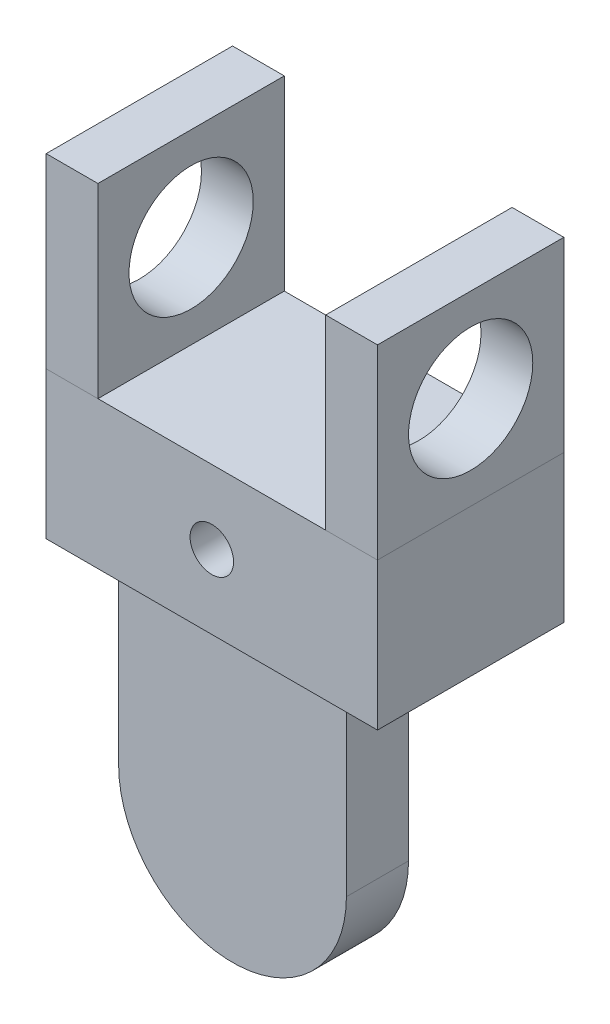
SolidWorks part; units mm, degrees
ref_plane "Front Plane" through (0, 0, 0) normal (0, 0, 1) x (1, 0, 0)
ref_plane "Top Plane" through (0, 0, 0) normal (0, 1, 0) x (1, 0, 0)
ref_plane "Right Plane" through (0, 0, 0) normal (1, 0, 0) x (0, 0, -1)
sketch "Sketch1" plane through (0, 0, 0) normal (0, 0, 1) x (1, 0, 0)
  circle A0 centre (0, 0) radius 1.505
  dimension "D1" = 3.01
extrude "Boss-Extrude1" add sketch "Sketch1" along normal blind 3.1
sketch "Sketch2" plane through (0, 0, 3.1) normal (0, 0, 1) x (1, 0, 0)
  line L0 (-5.5, 0) -> (-5.5, 8.72)
  line L1 (5.5, 0) -> (5.5, 8.72)
  line L2 (-5.5, 8.72) -> (5.5, 8.72)
  circle A1 centre (0, 0) radius 5.5
  circle M3 centre (0, 0) radius 1.505
  dimension "D1" = 11
  dimension "D2" = 8.72
  dimension "D3" = 8.72
extrude "Boss-Extrude2" add sketch "Sketch2" along normal blind 3 separate body contours A1 M3 | M3 | A1 L1 L2 L0
sketch "Sketch3" plane through (0, 8.72, 0) normal (0, 1, 0) x (1, 0, 0)
  line L0 (-5.5, -6.1) -> (-8, -6.1)
  line L1 (5.5, -6.1) -> (8, -6.1)
  line L2 (8, -6.1) -> (8, -7.1)
  line L3 (-8, -6.1) -> (8, -6.1)
  line L4 (-8, -6.1) -> (-8, 1.9)
  line L5 (-8, 1.9) -> (8, 1.9)
  line L6 (8, -6.1) -> (8, 1.9)
  line L7 (-8, -6.1) -> (-8, -7.1)
  line L8 (-8, -7.1) -> (8, -7.1)
  line M7 (5.5, -3.1) -> (-5.5, -3.1)
  line M8 (-5.5, -3.1) -> (-5.5, -6.1)
  line M9 (-5.5, -6.1) -> (5.5, -6.1)
  line M10 (5.5, -6.1) -> (5.5, -3.1)
  dimension "D1" = 2.5
  dimension "D2" = 2.5
  dimension "D3" = 8
  dimension "D4" = 1
  dimension "D5" = 1
extrude "Boss-Extrude4" add sketch "Sketch3" along normal blind 7.11 separate body contours M10 M7 M8 M9 | L1 L6 L5 L4 L0 M8 M7 M10 | L7 L8 L2 L1 L0 M9
sketch3d "3DSketch1"
  line L0 (-8, 15.83, 2.6) -> (-8, 20.33, 2.6) construction
  line L1 (-8, 15.83, -1.9) -> (-8, 24.83, -1.9)
  line L2 (-8, 15.83, -1.9) -> (-8, 15.83, 7.1)
  line L3 (-8, 15.83, 7.1) -> (-8, 24.83, 7.1)
  line L4 (-8, 24.83, -1.9) -> (-8, 24.83, 7.1)
  circle A0 centre (-8, 20.33, 2.6) radius 3
  point P9 (-5, 20.33, 2.6)
  dimension "D4" = 6
  dimension "D1" = 9
  dimension "D2" = 9
  dimension "D3" = 4.5
extrude "Boss-Extrude5" add sketch "3DSketch1" along a picked direction on the side against the normal blind 2.5 separate body contours L4 L3 L2 L1 | A0
sketch3d "3DSketch2"
  line L0 (8, 15.83, 2.6) -> (8, 20.33, 2.6) construction
  line L1 (8, 15.83, 7.1) -> (8, 24.83, 7.1)
  line L2 (8, 15.83, 7.1) -> (8, 15.83, -1.9)
  line L3 (8, 15.83, -1.9) -> (8, 24.83, -1.9)
  line L4 (8, 24.83, 7.1) -> (8, 24.83, -1.9)
  circle A0 centre (8, 20.33, 2.6) radius 3
  point P8 (11, 20.33, 2.6)
  dimension "D4" = 6
  dimension "D1" = 9
  dimension "D2" = 9
  dimension "D3" = 4.5
extrude "Boss-Extrude6" add sketch "3DSketch2" along a picked direction on the side against the normal blind 2.5 separate body
sketch "Sketch4" plane through (0, 0, -1.9) normal (0, 0, -1) x (-1, 0, 0)
  line L0 (0, 8.72) -> (0, 12.275) construction
  line L1 (8, 8.72) -> (-8, 8.72) construction
  circle A0 centre (0, 12.275) radius 1.05
  dimension "D2" = 2.1
  dimension "D1" = 3.555
extrude "Cut-Extrude1" cut sketch "Sketch4" against normal blind 9
